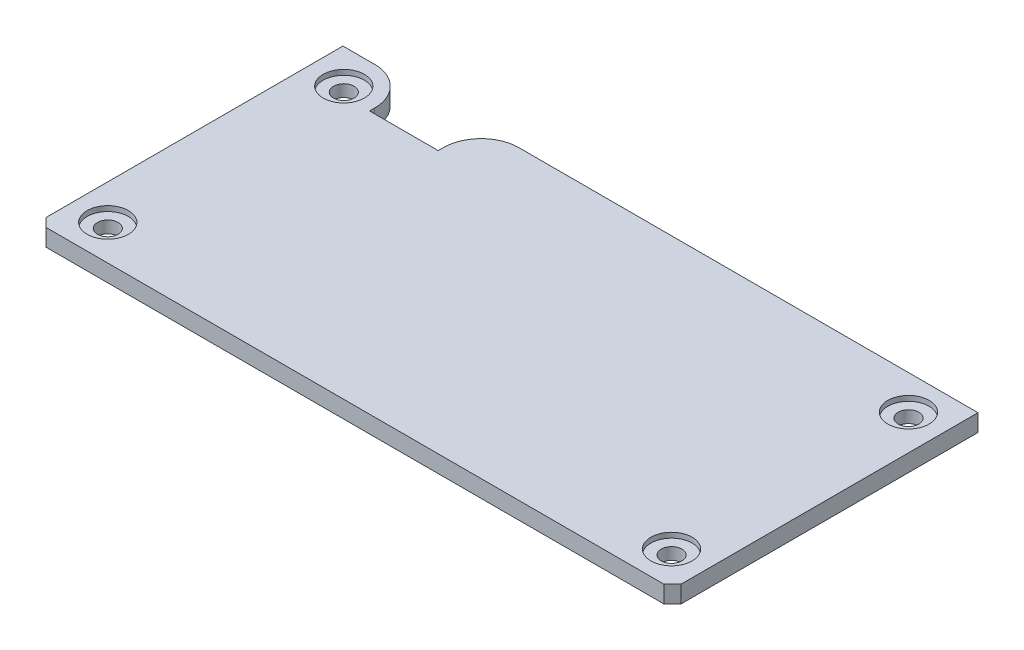
SolidWorks part; units mm, degrees
ref_plane "前视基准面" through (0, 0, 0) normal (0, 0, 1) x (1, 0, 0)
ref_plane "上视基准面" through (0, 0, 0) normal (0, 1, 0) x (1, 0, 0)
ref_plane "右视基准面" through (0, 0, 0) normal (1, 0, 0) x (0, 0, -1)
sketch "草图1" plane through (0, 0, 0) normal (0, 1, 0) x (1, 0, 0)
  line L1 (-37, 17.8) -> (37, 17.8)
  line L2 (-37, 17.8) -> (-37, -17.8)
  line L3 (-37, -17.8) -> (37, -17.8)
  line L4 (37, 17.8) -> (37, -17.8)
  line L5 (-37, 17.8) -> (37, -17.8) construction
  line L6 (-37, -17.8) -> (37, 17.8) construction
  point P0 (0, 0)
  dimension "D1" = 74
  dimension "D2" = 35.6
extrude "凸台-拉伸1" add sketch "草图1" along normal blind 2
chamfer "倒角1" distance 1 angle 45 2 edges at (37, 1, 17.8) (-37, 1, 17.8)
sketch "草图2" plane through (0, 2, 0) normal (0, 1, 0) x (1, 0, 0)
  circle A0 centre (32.9046, -13.8139) radius 1.2
  circle A1 centre (-32.9, -13.7) radius 1.2
  circle A2 centre (-32.9, 13.7991) radius 1.2
  circle A3 centre (32.9, 13.7991) radius 1.2
extrude "切除-拉伸1" cut sketch "草图2" against normal through all
sketch "草图3" plane through (0, 2, 0) normal (0, 1, 0) x (1, 0, 0)
  circle A0 centre (32.9046, -13.8139) radius 2.4
  circle A1 centre (-32.9, -13.7) radius 2.4
  circle A2 centre (32.9, 13.7991) radius 2.4
  circle A3 centre (-32.9, 13.7991) radius 2.4
  dimension "D1" = 4.8
extrude "切除-拉伸2" cut sketch "草图3" against normal blind 0.6
sketch "草图5" plane through (0, 2, 0) normal (0, 1, 0) x (1, 0, 0)
  line L0 (37, 17.8) -> (-37, 17.8) construction
  line L1 (-20.9, 12.8) -> (-28.9, 12.8)
  line L2 (-20.9, 12.8) -> (-20.9, 17.8)
  line L3 (-20.9, 17.8) -> (-28.9, 17.8)
  line L4 (-28.9, 12.8) -> (-28.9, 17.8)
  line L5 (-30.4, 11.2991) -> (-30.4, 16.2991) construction
  dimension "D1" = 1.5
  dimension "D2" = 5
  dimension "D3" = 8
extrude "切除-拉伸3" cut sketch "草图5" against normal through all
fillet "圆角1" radius 4.4 2 edges at (-28.9, 1, -17.8) (-20.9, 1, -17.8)
